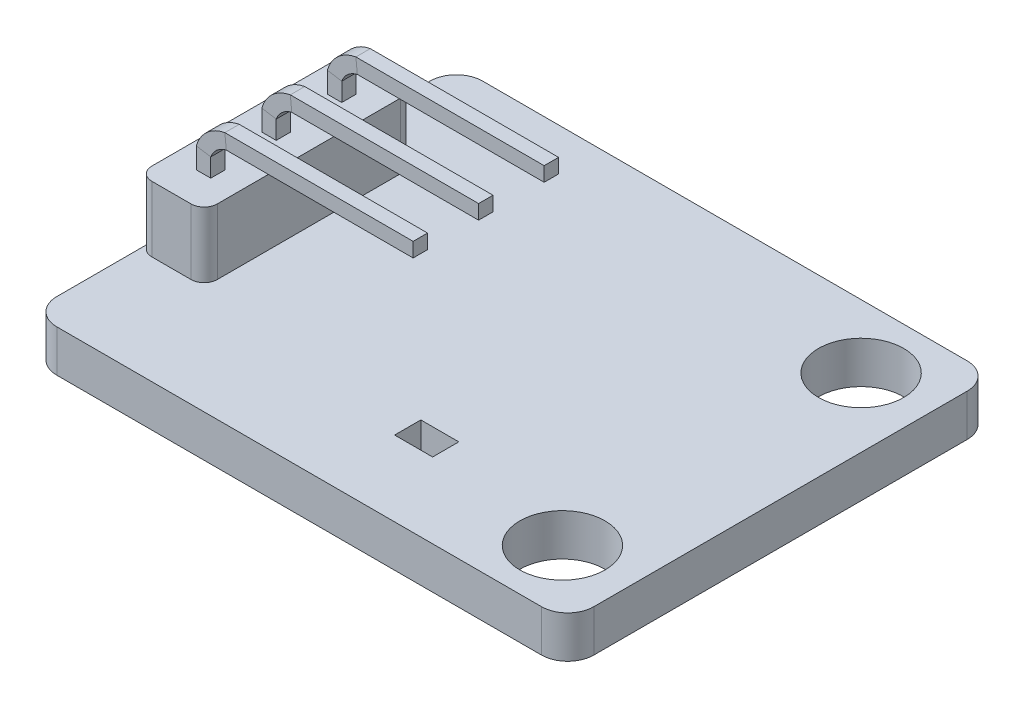
SolidWorks part; units mm, degrees
ref_plane "Front Plane" through (0, 0, 0) normal (0, 0, 1) x (1, 0, 0)
ref_plane "Top Plane" through (0, 0, 0) normal (0, 1, 0) x (1, 0, 0)
ref_plane "Right Plane" through (0, 0, 0) normal (1, 0, 0) x (0, 0, -1)
sketch "Sketch1" plane through (0, 0, 0) normal (0, 1, 0) x (1, 0, 0)
  line L0 (7.625, 7.325) -> (7.625, 8.125) construction
  line L1 (-10.25, -8.125) -> (10.25, -8.125)
  line L2 (-10.25, -8.125) -> (-10.25, 8.125)
  line L3 (-10.25, 8.125) -> (10.25, 8.125)
  line L4 (10.25, -8.125) -> (10.25, 8.125)
  line L5 (-10.25, -8.125) -> (10.25, 8.125) construction
  line L6 (-10.25, 8.125) -> (10.25, -8.125) construction
  line L7 (9.25, 5.7) -> (10.25, 5.7) construction
  line L8 (0, 0) -> (-5.4428, 0) construction
  circle A0 centre (7.625, 5.7) radius 1.625
  circle A1 centre (7.625, -5.7) radius 1.625
  point P0 (0, 0)
  dimension "D3" = 3.25
  dimension "D1" = 20.5
  dimension "D2" = 16.25
extrude "Boss-Extrude1" add sketch "Sketch1" along normal blind 1.6
fillet "Fillet1" radius 1 4 edges at (-10.25, 0.8, -8.125) (-10.25, 0.8, 8.125) (10.25, 0.8, -8.125) (10.25, 0.8, 8.125)
sketch "Sketch2" plane through (0, 1.6, 0) normal (0, 1, 0) x (1, 0, 0)
  line L0 (-10.25, 7.125) -> (-10.25, -7.125) construction
  line L1 (-10.25, -4) -> (-7.75, -4)
  line L2 (-10.25, -4) -> (-10.25, 4)
  line L3 (-10.25, 4) -> (-7.75, 4)
  line L4 (-7.75, -4) -> (-7.75, 4)
  line L5 (-10.25, -4) -> (-7.75, 4) construction
  line L6 (-10.25, 4) -> (-7.75, -4) construction
  point P0 (-9, 0)
  dimension "D1" = 8
  dimension "D2" = 2.5
extrude "Boss-Extrude2" add sketch "Sketch2" along normal blind 2.5
fillet "Fillet2" radius 0.5 4 edges at (-10.25, 2.85, -4) (-10.25, 2.85, 4) (-7.75, 2.85, -4) (-7.75, 2.85, 4)
ref_plane "Plane1" through (0, 0, 2.5) normal (0, 0, 1) x (1, 0, 0)
ref_plane "Plane2" through (0, 0, -2.5) normal (0, 0, 1) x (1, 0, 0)
sketch "Sketch5" plane through (0, 0, -2.5) normal (0, 0, 1) x (1, 0, 0)
  line L2 (-9, 4.1) -> (-9, 4.85)
  line L4 (-8.1601, 5.6) -> (-1, 5.6)
  arc A2 (-9, 4.85) -> (-8.1601, 5.6) centre (-7.9484, 4.5176) cw
sketch "Sketch6" plane through (0, 0, 2.5) normal (0, 0, 1) x (1, 0, 0)
  line L2 (-9, 4.1) -> (-9, 4.85)
  line L4 (-8.1601, 5.6) -> (-1, 5.6)
  arc A2 (-9, 4.85) -> (-8.1601, 5.6) centre (-7.9484, 4.5176) cw
sketch "Sketch8" plane through (0, 4.1, 0) normal (0, 1, 0) x (1, 0, 0)
  line L1 (-9.2761, 2.2279) -> (-8.7261, 2.2279)
  line L2 (-9.2761, 2.2279) -> (-9.2761, 2.7779)
  line L3 (-9.2761, 2.7779) -> (-8.7261, 2.7779)
  line L4 (-8.7261, 2.2279) -> (-8.7261, 2.7779)
  line L5 (-9.2761, 2.2279) -> (-8.7261, 2.7779) construction
  line L6 (-9.2761, 2.7779) -> (-8.7261, 2.2279) construction
  point P0 (-9.0011, 2.5029)
sketch "Sketch9" plane through (0, 4.1, 0) normal (0, 1, 0) x (1, 0, 0)
  line L1 (-9.275, -2.7736) -> (-8.725, -2.7736)
  line L2 (-9.275, -2.7736) -> (-9.275, -2.2236)
  line L3 (-9.275, -2.2236) -> (-8.725, -2.2236)
  line L4 (-8.725, -2.7736) -> (-8.725, -2.2236)
  line L5 (-9.275, -2.7736) -> (-8.725, -2.2236) construction
  line L6 (-9.275, -2.2236) -> (-8.725, -2.7736) construction
  point P0 (-9, -2.4986)
sweep "Sweep2" add profiles "Sketch8" path "Sketch5"
sweep "Sweep3" add profiles "Sketch9" path "Sketch6"
sketch "Sketch11" plane through (0, 0, 0) normal (0, 0, 1) x (1, 0, 0)
  line L2 (-9, 4.1) -> (-9, 4.85)
  line L3 (-8.1601, 5.6) -> (-1, 5.6)
  arc A1 (-8.1601, 5.6) -> (-9, 4.85) centre (-7.9484, 4.5176) ccw
sketch "Sketch12" plane through (0, 4.1, 0) normal (0, 1, 0) x (1, 0, 0)
  line L0 (-9, 0) -> (-8.1601, 0) construction
  line L1 (-9.275, -0.275) -> (-8.725, -0.275)
  line L2 (-9.275, -0.275) -> (-9.275, 0.275)
  line L3 (-9.275, 0.275) -> (-8.725, 0.275)
  line L4 (-8.725, -0.275) -> (-8.725, 0.275)
  line L5 (-9.275, -0.275) -> (-8.725, 0.275) construction
  line L6 (-9.275, 0.275) -> (-8.725, -0.275) construction
  point P0 (-9, 0)
sweep "Sweep4" add profiles "Sketch12" path "Sketch11"
sketch "Sketch13" plane through (0, 0, 0) normal (0, -1, 0) x (1, 0, 0)
  line L0 (1.5, 8.125) -> (1.5, 4.755) construction
  line L2 (-9.25, 8.125) -> (9.25, 8.125) construction
  line L3 (1.5, 4.755) -> (10.25, 4.755) construction
  line L4 (10.25, 7.125) -> (10.25, -7.125) construction
  line L6 (0.775, 4.255) -> (2.225, 4.255)
  line L7 (0.775, 4.255) -> (0.775, 5.255)
  line L8 (0.775, 5.255) -> (2.225, 5.255)
  line L9 (2.225, 4.255) -> (2.225, 5.255)
  line L10 (0.775, 4.255) -> (2.225, 5.255) construction
  line L11 (0.775, 5.255) -> (2.225, 4.255) construction
  dimension "D1" = 8.75
  dimension "D2" = 3.37
extrude "Cut-Extrude1" cut sketch "Sketch13" against normal blind 4
